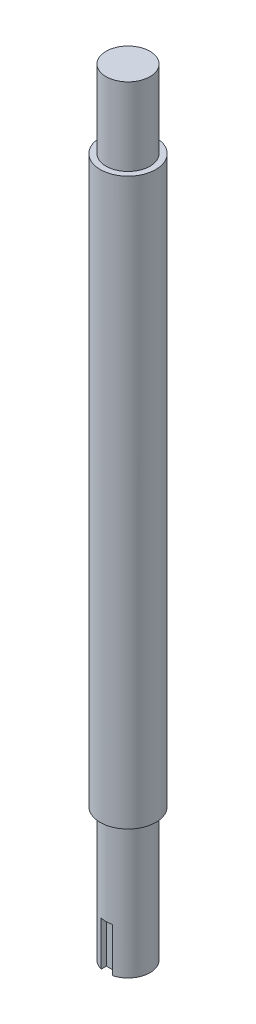
SolidWorks part; units mm, degrees
material "ASTM A36 Steel"
ref_plane "Front Plane" through (0, 0, 0) normal (0, 0, 1) x (1, 0, 0)
ref_plane "Top Plane" through (0, 0, 0) normal (0, 1, 0) x (1, 0, 0)
ref_plane "Right Plane" through (0, 0, 0) normal (1, 0, 0) x (0, 0, -1)
sketch "Sketch1" plane through (0, 0, 0) normal (0, 1, 0) x (1, 0, 0)
  circle A0 centre (0, 0) radius 15.875
  dimension "D1" = 31.75
extrude "Boss-Extrude1" add sketch "Sketch1" along normal mid plane 431.8
sketch "Sketch4" plane through (0, 215.9, 0) normal (0, 1, 0) x (1, 0, 0)
  circle A0 centre (0, 0) radius 12.5889
  circle A2 centre (0, 0) radius 15.875
  dimension "D1" = 25.1777
extrude "Cut-Extrude3" cut sketch "Sketch4" against normal blind 69.85
sketch "Sketch5" plane through (0, -215.9, 0) normal (0, -1, 0) x (1, 0, 0)
  circle A0 centre (0, 0) radius 12.5889
  circle A2 centre (0, 0) radius 15.875
  dimension "D1" = 25.1777
extrude "Cut-Extrude4" cut sketch "Sketch5" against normal blind 38.1
sketch "Sketch6" plane through (0, 0, 0) normal (0, 0, 1) x (1, 0, 0)
  line L0 (-245.1035, 0) -> (245.1035, 0) construction
  line L1 (0, -299.7313) -> (0, 299.7313) construction
  line L2 (-158.8976, -113.4364) -> (158.8976, -113.4364) construction
  line L3 (-12.5889, -215.9) -> (12.5889, -215.9) construction
  point P4 (0, 0)
  point P8 (0, 0)
  point P11 (0, -113.4364)
  dimension "D1" = 102.4636
sketch "Sketch7" plane through (0, -215.9, 0) normal (0, -1, 0) x (1, 0, 0)
  circle A0 centre (0, 0) radius 12.5889
extrude "Boss-Extrude2" add sketch "Sketch7" along normal blind 38.1
sketch "Sketch8" plane through (0, -254, 0) normal (0, -1, 0) x (1, 0, 0)
  line L0 (-34.5542, 0) -> (34.5542, 0) construction
  line L1 (0, -29.6857) -> (0, 29.6857) construction
  line L2 (-22.6147, -12.5889) -> (22.6147, -12.5889) construction
  line L3 (-3.175, 9.2297) -> (3.175, 9.2297)
  line L4 (-3.175, 15.7067) -> (3.175, 15.7067)
  line L5 (3.175, 15.7067) -> (3.175, 9.2297)
  line L6 (-3.175, 15.7067) -> (-3.175, 9.2297)
  point P5 (0, 0)
  point P9 (0, 0)
  point P12 (0, -12.5889)
  point P15 (0, 9.2297)
  point P18 (0, 15.7067)
  dimension "D1" = 6.35
  dimension "D2" = 21.8186
  dimension "D3" = 6.35
  dimension "D4" = 28.2956
extrude "Cut-Extrude5" cut sketch "Sketch8" against normal blind 25.4
sketch "Sketch9" plane through (0, 215.9, 0) normal (0, 1, 0) x (1, 0, 0)
  circle A0 centre (0, 0) radius 12.5889
extrude "Cut-Extrude6" cut sketch "Sketch9" against normal blind 25.4
